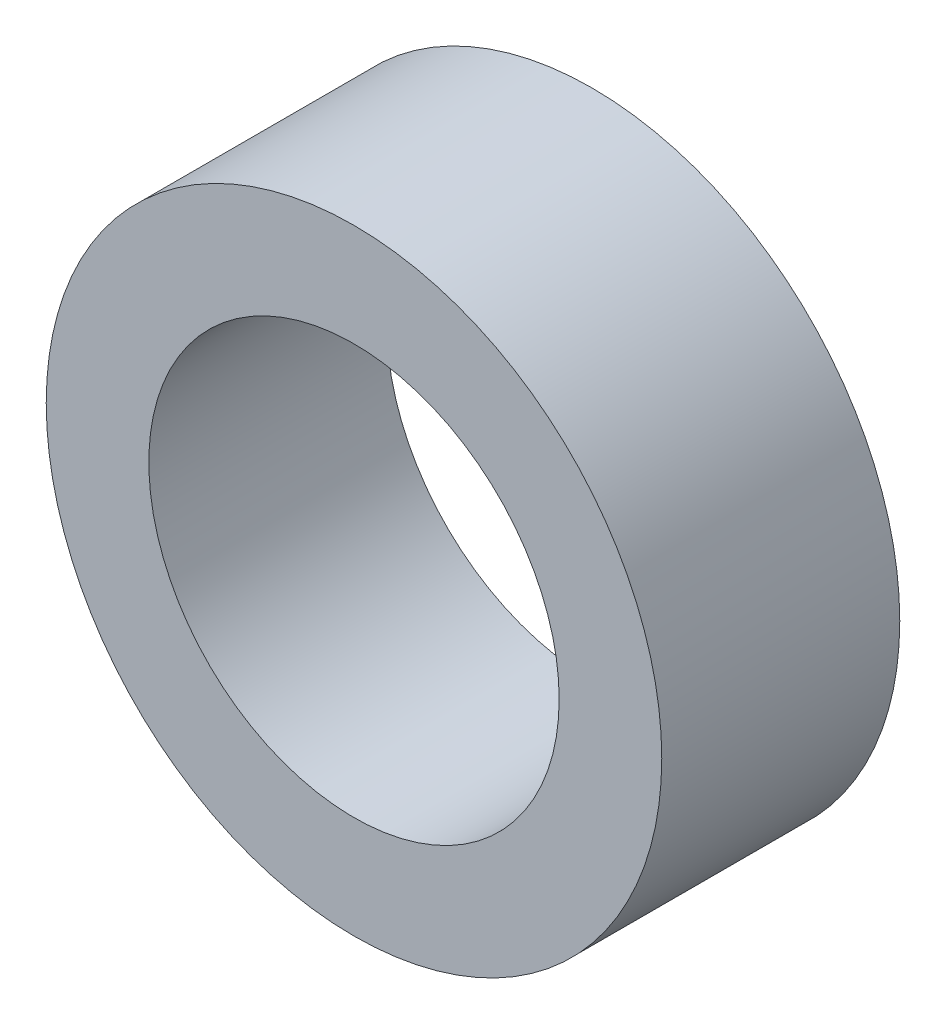
SolidWorks part; units mm, degrees
ref_plane "Front Plane" through (0, 0, 0) normal (0, 0, 1) x (1, 0, 0)
ref_plane "Top Plane" through (0, 0, 0) normal (0, 1, 0) x (1, 0, 0)
ref_plane "Right Plane" through (0, 0, 0) normal (1, 0, 0) x (0, 0, -1)
sketch "Sketch1" plane through (0, 0, 0) normal (0, 0, 1) x (1, 0, 0)
  circle A0 centre (0, 0) radius 5
  circle A1 centre (0, 0) radius 7.5
  dimension "D1" = 10
  dimension "D2" = 15
extrude "Boss-Extrude1" add sketch "Sketch1" along normal blind 5.8
